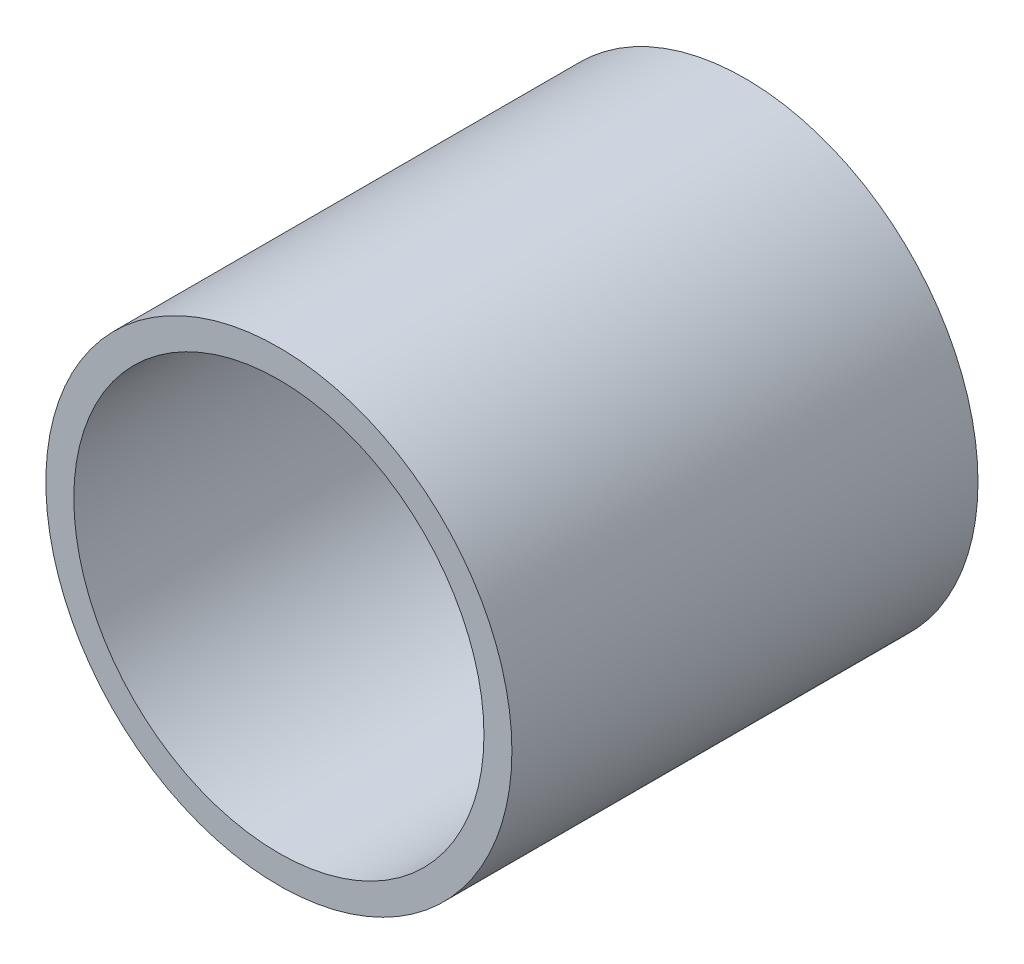
SolidWorks part; units mm, degrees
ref_plane "Front Plane" through (0, 0, 0) normal (0, 0, 1) x (1, 0, 0)
ref_plane "Top Plane" through (0, 0, 0) normal (0, 1, 0) x (1, 0, 0)
ref_plane "Right Plane" through (0, 0, 0) normal (1, 0, 0) x (0, 0, -1)
sketch "Sketch1" plane through (0, 0, 0) normal (0, 0, 1) x (1, 0, 0)
  circle A0 centre (0, 0) radius 25
  circle A1 centre (0, 0) radius 22
  dimension "D1" = 50
  dimension "D2" = 44
extrude "Boss-Extrude1" add sketch "Sketch1" along normal mid plane 50
